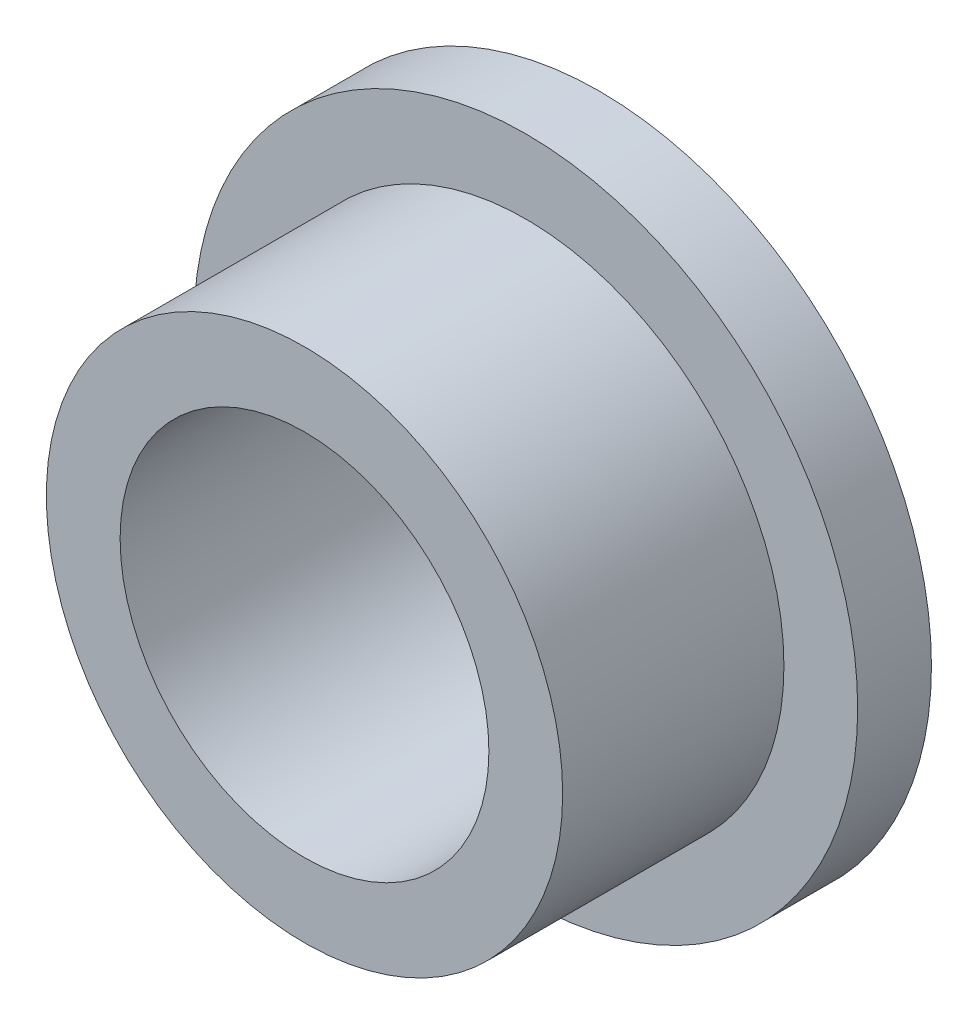
SolidWorks part; units mm, degrees
ref_plane "Front Plane" through (0, 0, 0) normal (0, 0, 1) x (1, 0, 0)
ref_plane "Top Plane" through (0, 0, 0) normal (0, 1, 0) x (1, 0, 0)
ref_plane "Right Plane" through (0, 0, 0) normal (1, 0, 0) x (0, 0, -1)
sketch "Sketch1" plane through (0, 0, 0) normal (0, 0, 1) x (1, 0, 0)
  circle A0 centre (0, 0) radius 3.9688
  circle A1 centre (0, 0) radius 7.1438
  dimension "D1" = 7.9375
  dimension "D2" = 14.2875
extrude "Boss-Extrude1" add sketch "Sketch1" along normal blind 6.35
sketch "Sketch2" plane through (0, 0, 6.35) normal (0, 0, 1) x (1, 0, 0)
  circle A0 centre (0, 0) radius 7.1438
  circle A1 centre (0, 0) radius 5.5562
  circle A2 centre (0, 0) radius 7.1438 construction
  dimension "D1" = 11.1125
extrude "Cut-Extrude2" cut sketch "Sketch2" against normal blind 4.7625
